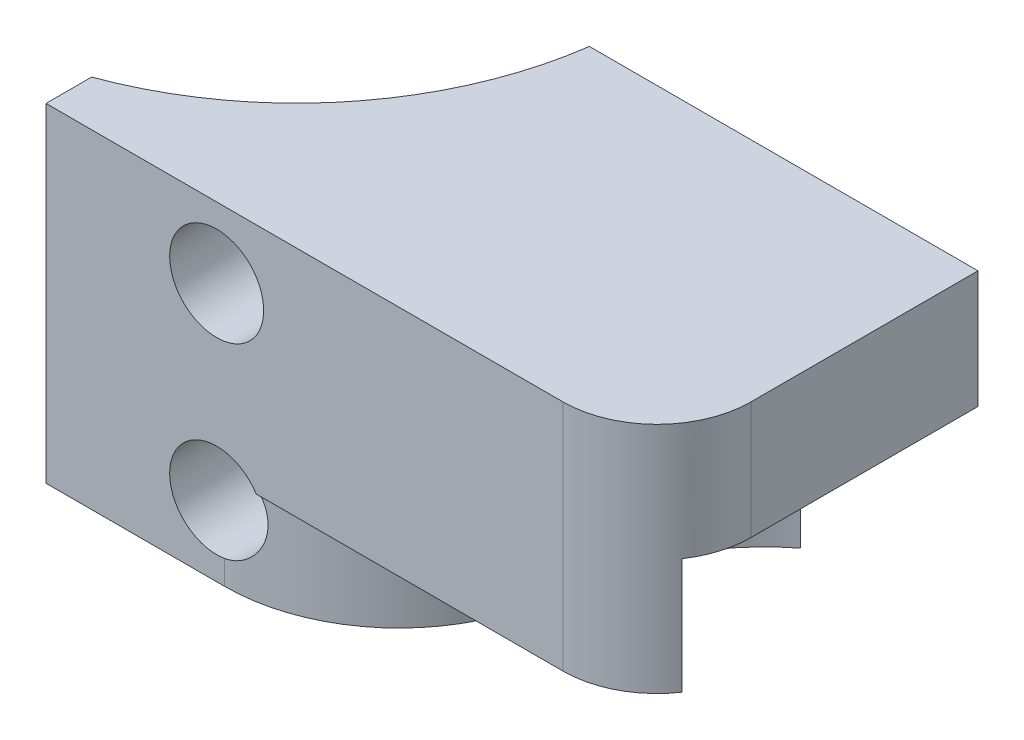
SolidWorks part; units mm, degrees
ref_plane "Front Plane" through (0, 0, 0) normal (0, 0, 1) x (1, 0, 0)
ref_plane "Top Plane" through (0, 0, 0) normal (0, 1, 0) x (1, 0, 0)
ref_plane "Right Plane" through (0, 0, 0) normal (1, 0, 0) x (0, 0, -1)
sketch "Sketch1" plane through (0, 0, 0) normal (0, 1, 0) x (1, 0, 0)
  line L0 (-23.5, -17.1533) -> (41.5, -17.1533)
  line L6 (-23.5, -17.1533) -> (-23.5, 17)
  line L7 (41.5, -17.1533) -> (41.5, -12.1533)
  line L8 (-23.5, 17) -> (24, 17)
  line L19 (24, -0.6969) -> (24, 17)
  circle A1 centre (-36, 22) radius 36.5
  circle A3 centre (36.5, -0.6969) radius 12.5
  point P0 (0, 0)
  dimension "D3" = 73
  dimension "D4" = 12.5
  dimension "D6" = 25
  dimension "D7" = 17.6969
  dimension "D8" = 60
  dimension "D1" = 36
  dimension "D2" = 17
  dimension "D5" = 5
  dimension "D9" = 47.5
  dimension "D10" = 65
  dimension "D11" = 5
extrude "Boss-Extrude1" add sketch "Sketch1" along normal blind 35
sketch "Sketch2" plane through (24, 0, 0) normal (1, 0, 0) x (0, 0, -1)
  line L1 (17, 35) -> (-0.6969, 35)
  line L2 (17, 35) -> (17, 22.5)
  line L3 (17, 22.5) -> (-0.6969, 22.5)
  line L4 (-0.6969, 35) -> (-0.6969, 22.5)
  dimension "D1" = 17.6969
  dimension "D2" = 12.5
extrude "Boss-Extrude2" add sketch "Sketch2" along normal up to surface (17.5 mm away) up to face at (41.5, 17.5, 14.6533)
sketch "Sketch3" plane through (0, 0, 0.6969) normal (0, 0, 1) x (1, 0, 0)
  line L0 (41.5, 22.5) -> (24, 22.5) construction
  line L1 (41.5, 35) -> (23.9231, 35)
  line L2 (41.5, 35) -> (41.5, 22.5)
  line L3 (41.5, 22.5) -> (23.9231, 22.5)
  line L4 (23.9231, 35) -> (23.9231, 22.5)
  dimension "D1" = 17.5769
extrude "Boss-Extrude3" add sketch "Sketch3" along normal up to surface (11.4564 mm away)
sketch "Sketch6" plane through (0, 0, -17) normal (0, 0, -1) x (-1, 0, 0)
  line L0 (-0.1559, 35) -> (-0.1559, 0) construction
  line L1 (23.5, 35) -> (-0.1559, 35) construction
  line L2 (23.5, 0) -> (-41.5, 0) construction
  circle A0 centre (5.3441, 7.5) radius 5
  circle A1 centre (5.3441, 27.5) radius 5
  dimension "D1" = 10
  dimension "D2" = 10
  dimension "D4" = 7.5
  dimension "D5" = 7.5
  dimension "D3" = 5.5
extrude "Cut-Extrude4" cut sketch "Sketch6" against normal up to surface (34.1533 mm away) up to face at (9, 17.5, 17.1533)
sketch "Sketch7" plane through (0, 0, 0) normal (0, -1, 0) x (1, 0, 0)
  line L0 (-23.5, 17.1533) -> (-23.5, -17) construction
  line L1 (-23.5, -17) -> (24, -17) construction
  circle A0 centre (36.5, 0.6969) radius 22.5
  dimension "D1" = 45
  dimension "D2" = 60
  dimension "D3" = 17.6969
extrude "Cut-Extrude5" cut sketch "Sketch7" against normal up to surface (10.195 mm away)
sketch "Sketch8" plane through (0, 0, 0) normal (0, -1, 0) x (1, 0, 0)
  line L1 (-23.5, 17.1533) -> (41.5, 17.1533) construction
  line L2 (-4.5, 17.1533) -> (41.5, 17.1533)
  line L3 (41.5, 17.1533) -> (41.5, -17)
  line L4 (41.5, -17) -> (22.605, -17)
  line L5 (22.605, -17) -> (14.0202, -0.2568)
  arc A0 (14.0202, -0.2568) -> (-4.5, 17.1533) centre (-4.5, -1.4023) ccw
  arc A2 (21.1561, 17.1533) -> (22.605, -17) centre (36.5, 0.6969) ccw construction
  dimension "D1" = 46
extrude "Cut-Extrude6" cut sketch "Sketch8" against normal up to surface (10.195 mm away)
fillet "Fillet1" radius 10 1 edges at (41.5, 22.5975, 17.1533)
